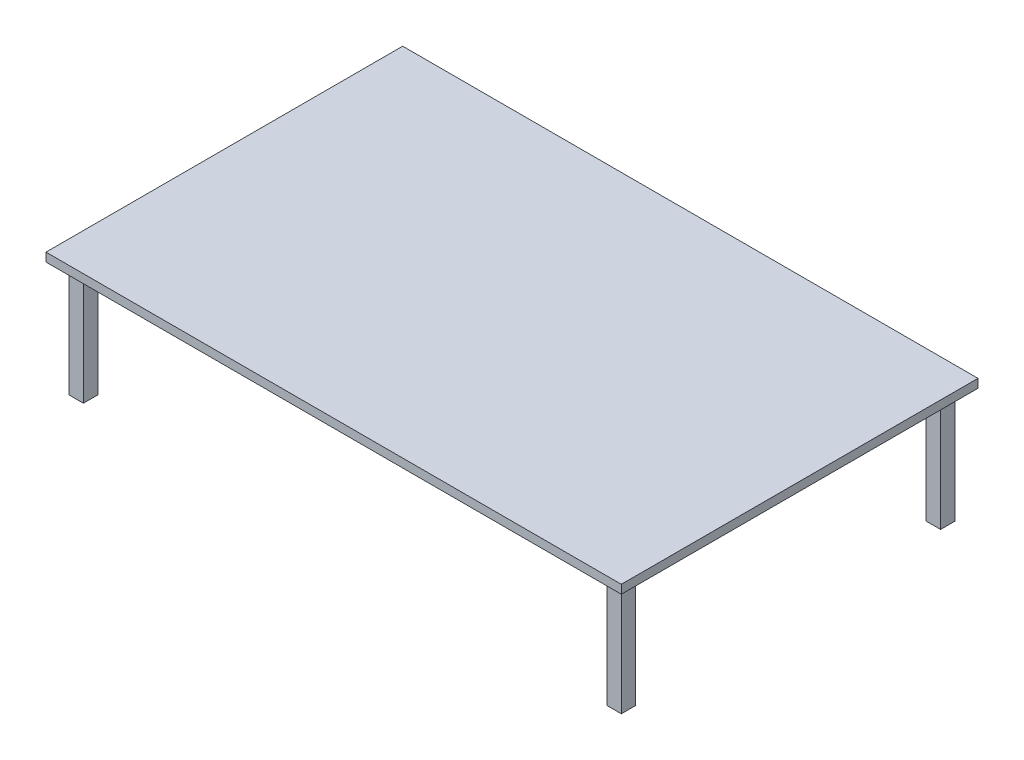
SolidWorks part; units mm, degrees
material "Plain Carbon Steel"
ref_plane "Front Plane" through (0, 0, 0) normal (0, 0, 1) x (1, 0, 0)
ref_plane "Top Plane" through (0, 0, 0) normal (0, 1, 0) x (1, 0, 0)
ref_plane "Right Plane" through (0, 0, 0) normal (1, 0, 0) x (0, 0, -1)
sketch "Sketch1" plane through (0, 0, 0) normal (0, 1, 0) x (1, 0, 0)
  line L0 (0, 0) -> (-359.8255, 0) construction
  line L1 (-480, -290) -> (-455, -290)
  line L2 (-480, -290) -> (-480, -265)
  line L3 (-480, -265) -> (-455, -265)
  line L4 (-455, -290) -> (-455, -265)
  line L5 (-455, 290) -> (-455, 265)
  line L6 (-480, 265) -> (-455, 265)
  line L7 (-480, 290) -> (-480, 265)
  line L8 (-480, 290) -> (-455, 290)
  line L9 (0, 0) -> (0, 215.2679) construction
  line L10 (480, 290) -> (455, 290)
  line L11 (480, 290) -> (480, 265)
  line L12 (480, 265) -> (455, 265)
  line L13 (455, 290) -> (455, 265)
  line L14 (455, -290) -> (455, -265)
  line L15 (480, -265) -> (455, -265)
  line L16 (480, -290) -> (480, -265)
  line L17 (480, -290) -> (455, -290)
  line L19 (500, 310) -> (-500, 310) construction
  line L20 (500, 310) -> (500, -310) construction
  line L21 (500, -310) -> (-500, -310) construction
  line L22 (-500, 310) -> (-500, -310) construction
  line L23 (500, 310) -> (-500, -310) construction
  line L24 (500, -310) -> (-500, 310) construction
  dimension "D1" = 25
  dimension "D2" = 25
  dimension "D3" = 20
  dimension "D4" = 20
  dimension "D5" = 1000
  dimension "D6" = 620
extrude "Boss-Extrude1" add sketch "Sketch1" along normal blind 200
sketch "Sketch2" plane through (0, 200, 0) normal (0, 1, 0) x (1, 0, 0)
  line L5 (500, 310) -> (500, -310) construction
  line L6 (500, -310) -> (-500, -310) construction
  line L8 (500, 310) -> (-500, 310) construction
  line L9 (-500, 310) -> (-500, -310) construction
  line L10 (500, 310) -> (500, -310)
  line L11 (500, -310) -> (-500, -310)
  line L12 (500, 310) -> (-500, 310)
  line L13 (-500, 310) -> (-500, -310)
extrude "Boss-Extrude2" add sketch "Sketch2" along normal blind 15
